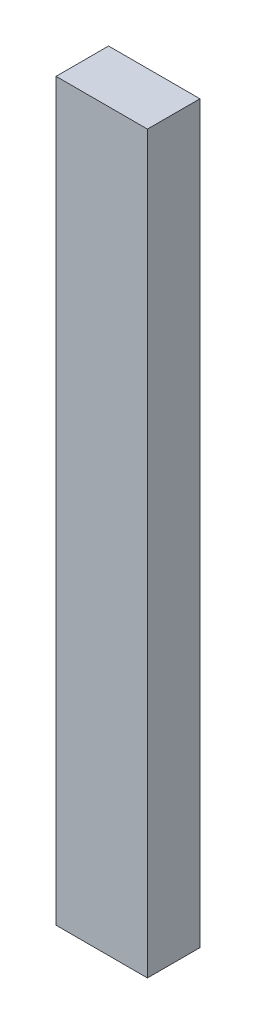
SolidWorks part; units mm, degrees
ref_plane "Front Plane" through (0, 0, 0) normal (0, 0, 1) x (1, 0, 0)
ref_plane "Top Plane" through (0, 0, 0) normal (0, 1, 0) x (1, 0, 0)
ref_plane "Right Plane" through (0, 0, 0) normal (1, 0, 0) x (0, 0, -1)
sketch "Sketch2" plane through (0, 0, 0) normal (0, 1, 0) x (1, 0, 0)
  line L1 (-4.35, -2.5) -> (4.35, -2.5)
  line L2 (-4.35, -2.5) -> (-4.35, 2.5)
  line L3 (-4.35, 2.5) -> (4.35, 2.5)
  line L4 (4.35, -2.5) -> (4.35, 2.5)
  line L5 (-4.35, -2.5) -> (4.35, 2.5) construction
  line L6 (-4.35, 2.5) -> (4.35, -2.5) construction
  point P0 (0, 0)
  dimension "D1" = 8.7
  dimension "D2" = 5
extrude "Boss-Extrude1" add sketch "Sketch2" along normal blind 70 contours L2 L1 L4 L3
